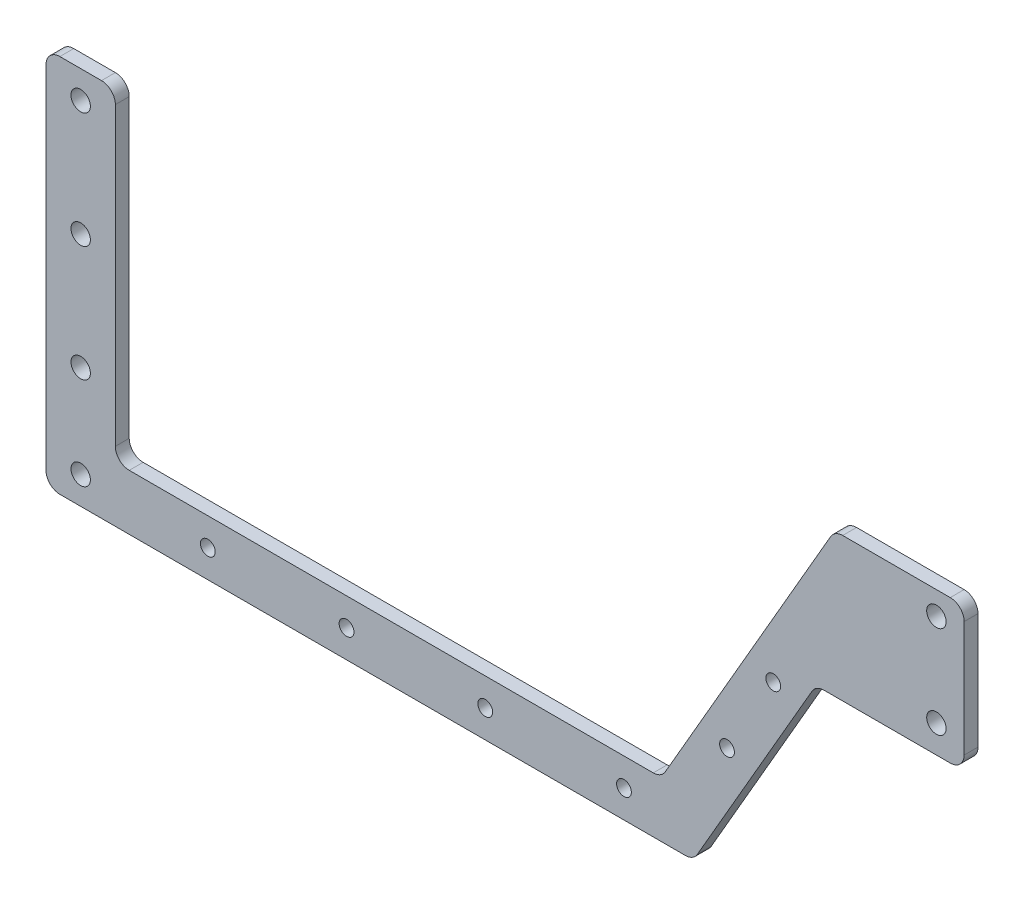
SolidWorks part; units mm, degrees
material "Thornel Mat VMA"
ref_plane "前视基准面" through (0, 0, 0) normal (0, 0, 1) x (1, 0, 0)
ref_plane "上视基准面" through (0, 0, 0) normal (0, 1, 0) x (1, 0, 0)
ref_plane "右视基准面" through (0, 0, 0) normal (1, 0, 0) x (0, 0, -1)
other "Configuration Table"
sketch "草图1" plane through (0, 0, 0) normal (0, 0, 1) x (1, 0, 0)
  line L0 (0, 0) -> (0, 31)
  line L1 (0, 31) -> (-28, 31)
  line L2 (-28, 31) -> (-65.5, -33.9519)
  line L3 (-65.5, -33.9519) -> (-183.5718, -33.9519)
  line L4 (-183.5718, -33.9519) -> (-183.5718, 36.0481)
  line L5 (-183.5718, 36.0481) -> (-198.5718, 36.0481)
  line L6 (-198.5718, 36.0481) -> (-198.5718, -45.9519)
  line L7 (-198.5718, -45.9519) -> (-58.5718, -45.9519)
  line L8 (-58.5718, -45.9519) -> (-32.0415, 0)
  line L9 (-32.0415, 0) -> (0, 0)
  line L10 (-6, 31) -> (-6, 0) construction
  circle A0 centre (-6, 26) radius 2.1
  circle A1 centre (-6, 6) radius 2.1
  dimension "D11" = 4.2
  dimension "D12" = 20
  dimension "D13" = 5
  dimension "D1" = 12
  dimension "D2" = 12
  dimension "D3" = 15
  dimension "D4" = 70
  dimension "D5" = 140
  dimension "D6" = 120
  dimension "D7" = 75
  dimension "D8" = 31
  dimension "D9" = 28
  dimension "D10" = 6
extrude "凸台-拉伸1" add sketch "草图1" along normal blind 3
fillet "圆角2" radius 3 10 edges at (-32.0415, 0, 1.5) (-58.5718, -45.9519, 1.5) (-198.5718, -45.9519, 1.5) (-183.5718, 36.0481, 1.5) (-183.5718, -33.9519, 1.5) (-65.5, -33.9519, 1.5) (-28, 31, 1.5) (0, 31, 1.5) (0, 0, 1.5) (-198.5718, 36.0481, 1.5)
sketch "草图3" plane through (0, 0, 3) normal (0, 0, 1) x (1, 0, 0)
  line L0 (-191.0718, 36.0481) -> (-191.0718, -39.9519) construction
  line L1 (-186.5718, 36.0481) -> (-195.5718, 36.0481) construction
  line L2 (-191.0718, -39.9519) -> (-62.0359, -39.9519) construction
  line L3 (-62.0359, -39.9519) -> (-30.1136, 15.3391) construction
  line L4 (-67.2321, -33.9519) -> (-180.5718, -33.9519) construction
  line L5 (-57.7058, -44.4519) -> (-32.9075, -1.5) construction
  line L6 (-3, 31) -> (-26.2679, 31) construction
  line L7 (-198.5718, 33.0481) -> (-198.5718, -42.9519) construction
  circle A0 centre (-41.2791, -4) radius 1.6
  circle A1 centre (-51.2791, -21.3205) radius 1.6
  circle A2 centre (-73.5718, -39.9519) radius 1.6
  circle A3 centre (-103.5718, -39.9519) radius 1.6
  circle A4 centre (-133.5718, -39.9519) radius 1.6
  circle A5 centre (-191.0718, -19.9519) radius 2.1
  circle A6 centre (-191.0718, 5.0481) radius 2.1
  circle A7 centre (-191.0718, 30.0481) radius 2.1
  circle A8 centre (-191.0718, -39.9519) radius 2.1
  circle A9 centre (-163.5718, -39.9519) radius 1.6
  dimension "D3" = 3.2
  dimension "D4" = 20
  dimension "D5" = 35
  dimension "D6" = 30
  dimension "D7" = 30
  dimension "D8" = 125
  dimension "D9" = 4.2
  dimension "D10" = 25
  dimension "D11" = 25
  dimension "D12" = 20
  dimension "D13" = 4.2
  dimension "D14" = 3.2
  dimension "D15" = 30
  dimension "D1" = 6
  dimension "D2" = 6
extrude "切除-拉伸2" cut sketch "草图3" against normal blind 3
